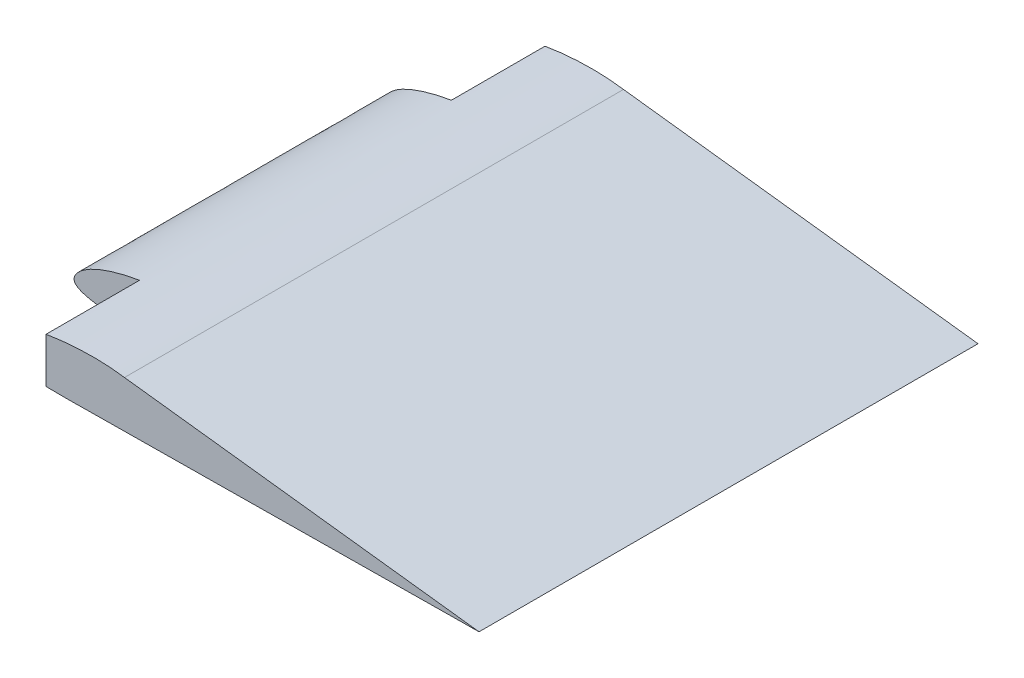
SolidWorks part; units mm, degrees
material "EPP"
ref_plane "Front Plane" through (0, 0, 0) normal (0, 0, 1) x (1, 0, 0)
ref_plane "Top Plane" through (0, 0, 0) normal (0, 1, 0) x (1, 0, 0)
ref_plane "Right Plane" through (0, 0, 0) normal (1, 0, 0) x (0, 0, -1)
sketch "ArbitraryAirfoil" plane through (0, 0, 0) normal (0, 0, 1) x (1, 0, 0)
  line L3 (0, 35.3465) -> (0, -15.2384) construction
  line L6 (203.1999, 14.8055) -> (203.1999, -9.937) construction
  line L7 (0, -0.0006) -> (203.1999, -0.0006) construction
  line L9 (203.0209, 6.1616) -> (45.2441, 4.5477)
  line L10 (58.6413, 23.6589) -> (203.0209, 6.1616)
  line L11 (0, 14.4503) -> (0, 4.9684) construction
  spline S2 degree 3 poles (45.2441, 4.5477) (17.8592, 4.0134) (-2.2466, 5.758) (3.9069, 20.4435) (37.8051, 26.7803) (58.6413, 23.6589) knots 0 0 0 0 0.290581 0.390581 1 1 1 1
  point P18 (50.8, 4.6844)
  dimension "D1" = 203.1999
extrude "Airfoil" add sketch "ArbitraryAirfoil" along normal blind 203.2
ref_plane "Plane1" through (0, 0, 101.6) normal (0, 0, 1) x (1, 0, 0)
sketch "Sketch2" plane through (0, 0, 0) normal (0, 1, 0) x (1, 0, 0)
  line L0 (0, -38.1) -> (26.67, -38.1)
  line L1 (0, -203.2) -> (26.67, -203.2)
  line L2 (0, -203.2) -> (0, -165.1)
  line L3 (0, -165.1) -> (26.67, -165.1)
  line L4 (26.67, -203.2) -> (26.67, -165.1)
  line L5 (0, -38.1) -> (0, 0)
  line L6 (0, 0) -> (26.67, 0)
  line L7 (26.67, -38.1) -> (26.67, 0)
  dimension "D1" = 38.1
  dimension "D2" = 26.67
  dimension "D3" = 38.1
  dimension "D4" = 26.67
extrude "Cut-Extrude1" cut sketch "Sketch2" against normal blind 0.254 and the other way up to next
